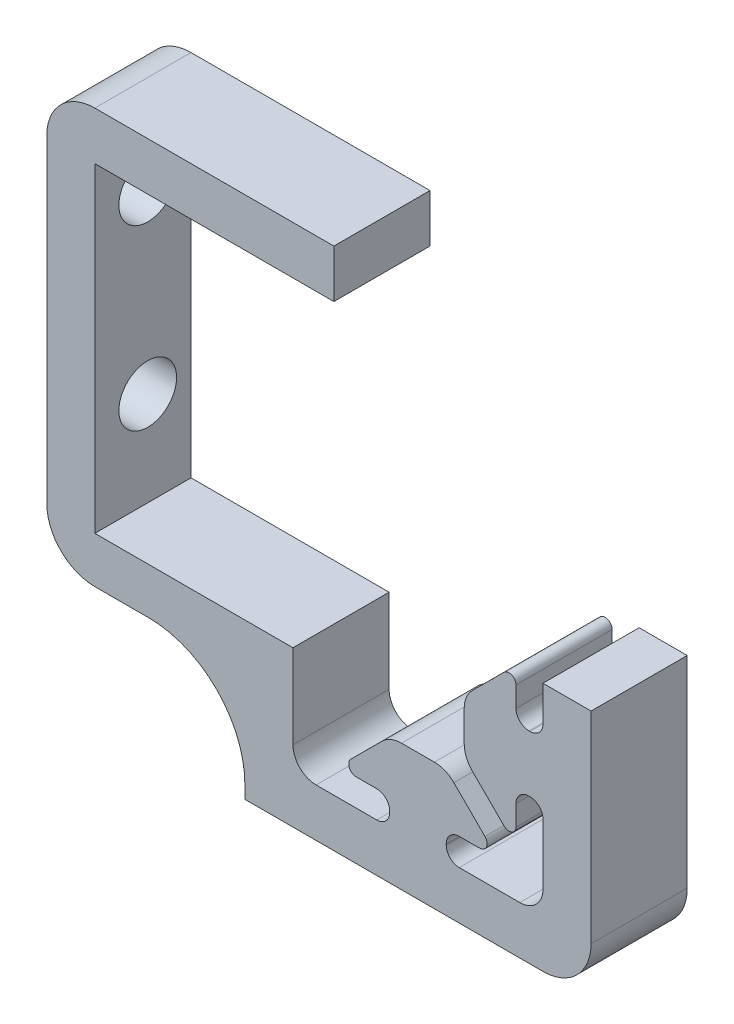
SolidWorks part; units mm, degrees
ref_plane "Front Plane" through (0, 0, 0) normal (0, 0, 1) x (1, 0, 0)
ref_plane "Top Plane" through (0, 0, 0) normal (0, 1, 0) x (1, 0, 0)
ref_plane "Right Plane" through (0, 0, 0) normal (1, 0, 0) x (0, 0, -1)
sketch "Sketch1" plane through (0, 0, 0) normal (0, 0, 1) x (1, 0, 0)
  line L0 (-10.5918, -13) -> (-4.3059, -13)
  line L1 (-4.3059, -13) -> (-4.2875, -13)
  line L2 (-2.9385, -11.651) -> (-2.9385, -11.5392)
  line L3 (-4.2875, -10.1902) -> (-6.4164, -10.1902)
  line L4 (-6.9677, -8.8575) -> (-3.7403, -5.636)
  line L5 (-1.7093, -4.7958) -> (1.7093, -4.7958)
  line L6 (3.7403, -5.636) -> (6.9677, -8.8575)
  line L7 (6.4164, -10.1902) -> (4.2875, -10.1902)
  line L8 (2.9385, -11.5392) -> (2.9385, -11.651)
  line L9 (4.2875, -13) -> (5.3216, -13)
  line L10 (5.3216, -13) -> (10.5918, -13)
  line L11 (13, -10.5918) -> (13, -5.3171)
  line L12 (13, -5.3171) -> (13, -4.2875)
  line L13 (11.651, -2.9385) -> (11.5392, -2.9385)
  line L14 (10.1902, -4.2875) -> (10.1902, -6.4021)
  line L15 (8.949, -6.917) -> (5.6529, -3.6284)
  line L16 (4.8085, -1.5932) -> (4.8085, 1.5932)
  line L17 (5.6529, 3.6284) -> (8.949, 6.917)
  line L18 (10.1902, 6.4021) -> (10.1902, 4.2875)
  line L19 (11.5392, 2.9385) -> (11.651, 2.9385)
  line L20 (13, 4.2875) -> (13, 5.3171)
  line L21 (13, 5.3171) -> (13, 10.5918) construction
  line L22 (10.5918, 13) -> (5.3216, 13) construction
  line L23 (5.3216, 13) -> (4.2875, 13) construction
  line L24 (2.9385, 11.651) -> (2.9385, 11.5392) construction
  line L25 (4.2875, 10.1902) -> (6.4768, 10.1902) construction
  line L26 (6.9951, 8.9367) -> (3.6864, 5.6355) construction
  line L27 (1.6558, 4.7958) -> (-1.6558, 4.7958) construction
  line L28 (-3.6864, 5.6355) -> (-6.9951, 8.9367) construction
  line L29 (-6.4768, 10.1902) -> (-4.2875, 10.1902) construction
  line L30 (-2.9385, 11.5392) -> (-2.9385, 11.651) construction
  line L31 (-4.2875, 13) -> (-4.3059, 13) construction
  line L32 (-4.3059, 13) -> (-10.5918, 13) construction
  line L33 (-13, 10.5918) -> (-13, 5.3171) construction
  line L34 (-13, 5.3171) -> (-13, 4.2875) construction
  line L35 (-11.651, 2.9385) -> (-11.5392, 2.9385) construction
  line L36 (-10.1902, 4.2875) -> (-10.1902, 6.4021) construction
  line L37 (-8.949, 6.917) -> (-5.6529, 3.6284) construction
  line L38 (-4.8085, 1.5932) -> (-4.8085, -1.5932) construction
  line L39 (-5.6529, -3.6284) -> (-8.949, -6.917) construction
  line L40 (-10.1902, -6.4021) -> (-10.1902, -4.2875) construction
  line L41 (-11.5392, -2.9385) -> (-11.651, -2.9385) construction
  line L42 (-13, -4.2875) -> (-13, -10.5918)
  line L44 (13, 5.3171) -> (13, 7.9544)
  line L45 (-33.4, 31.3527) -> (-13, 31.3527) construction
  line L46 (-33.4, 31.3527) -> (-33.4, -1.6473) construction
  line L47 (-33.4, -1.6473) -> (-13, -1.6473) construction
  line L48 (-13, 31.3527) -> (-13, -1.6473) construction
  line L49 (13, 7.9544) -> (18, 7.9544)
  line L50 (18, 7.9544) -> (18, -18)
  line L51 (18, -18) -> (-18, -18)
  line L52 (-18, -18) -> (-18, -6.6473)
  line L53 (-18, -6.6473) -> (-38.6, -6.6473)
  line L54 (-38.6, -6.6473) -> (-38.6, 36.4527)
  line L55 (-38.6, 36.4527) -> (-8.7453, 36.4527)
  line L56 (-8.7453, 36.4527) -> (-8.7453, 31.4527)
  line L57 (-8.7453, 31.4527) -> (-33.6, 31.4527)
  line L58 (-33.6, 31.4527) -> (-33.6, -1.8473)
  line L59 (-33.6, -1.8473) -> (-13, -1.8473)
  line L60 (-13, -1.8473) -> (-13, -4.2875)
  line L88 (-7.1797, -8.6452) -> (-3.9523, -5.4237) construction
  line L89 (-1.7093, -4.4958) -> (1.7093, -4.4958) construction
  line L90 (3.9523, -5.4237) -> (7.1797, -8.6452) construction
  line L91 (6.4164, -10.4902) -> (4.2875, -10.4902) construction
  line L92 (3.2385, -11.5392) -> (3.2385, -11.651) construction
  line L93 (4.2875, -12.7) -> (5.3216, -12.7) construction
  line L94 (5.3216, -12.7) -> (10.5918, -12.7) construction
  line L95 (12.7, -10.5918) -> (12.7, -5.3171) construction
  line L96 (12.7, -5.3171) -> (12.7, -4.2875) construction
  line L97 (11.651, -3.2385) -> (11.5392, -3.2385) construction
  line L98 (10.4902, -4.2875) -> (10.4902, -6.4021) construction
  line L99 (8.7371, -7.1294) -> (5.441, -3.8408) construction
  line L100 (4.5085, -1.5932) -> (4.5085, 1.5932) construction
  line L101 (5.441, 3.8408) -> (8.7371, 7.1294) construction
  line L102 (10.4902, 6.4021) -> (10.4902, 4.2875) construction
  line L103 (11.5392, 3.2385) -> (11.651, 3.2385) construction
  line L104 (12.7, 4.2875) -> (12.7, 5.3171) construction
  line L105 (12.7, 5.3171) -> (12.7, 10.5918) construction
  line L106 (10.5918, 12.7) -> (5.3216, 12.7) construction
  line L107 (5.3216, 12.7) -> (4.2875, 12.7) construction
  line L108 (3.2385, 11.651) -> (3.2385, 11.5392) construction
  line L109 (4.2875, 10.4902) -> (6.4768, 10.4902) construction
  line L110 (7.207, 8.7244) -> (3.8983, 5.4232) construction
  line L111 (1.6558, 4.4958) -> (-1.6558, 4.4958) construction
  line L112 (-3.8983, 5.4232) -> (-7.207, 8.7244) construction
  line L113 (-6.4768, 10.4902) -> (-4.2875, 10.4902) construction
  line L114 (-3.2385, 11.5392) -> (-3.2385, 11.651) construction
  line L115 (-4.2875, 12.7) -> (-4.3059, 12.7) construction
  line L116 (-4.3059, 12.7) -> (-10.5918, 12.7) construction
  line L117 (-12.7, 10.5918) -> (-12.7, 5.3171) construction
  line L118 (-12.7, 5.3171) -> (-12.7, 4.2875) construction
  line L119 (-11.651, 3.2385) -> (-11.5392, 3.2385) construction
  line L120 (-10.4902, 4.2875) -> (-10.4902, 6.4021) construction
  line L121 (-8.7371, 7.1294) -> (-5.441, 3.8408) construction
  line L122 (-4.5085, 1.5932) -> (-4.5085, -1.5932) construction
  line L123 (-5.441, -3.8408) -> (-8.7371, -7.1294) construction
  line L124 (-10.4902, -6.4021) -> (-10.4902, -4.2875) construction
  line L125 (-11.5392, -3.2385) -> (-11.651, -3.2385) construction
  line L126 (-12.7, -4.2875) -> (-12.7, -5.3171) construction
  line L127 (-12.7, -5.3171) -> (-12.7, -10.5918) construction
  line L128 (-10.5918, -12.7) -> (-4.3059, -12.7) construction
  line L129 (-4.3059, -12.7) -> (-4.2875, -12.7) construction
  line L130 (-3.2385, -11.651) -> (-3.2385, -11.5392) construction
  line L131 (-4.2875, -10.4902) -> (-6.4164, -10.4902) construction
  line L132 (-13, -4.2875) -> (-13, -5.3171) construction
  line L133 (-13, -5.3171) -> (-13, -10.5918) construction
  arc A0 (-4.2875, -13) -> (-2.9385, -11.651) centre (-4.2875, -11.651) ccw
  arc A2 (-2.9385, -11.5392) -> (-4.2875, -10.1902) centre (-4.2875, -11.5392) ccw
  arc A3 (-6.9677, -8.8575) -> (-6.4164, -10.1902) centre (-6.4164, -9.4098) ccw
  arc A4 (-1.7093, -4.7958) -> (-3.7403, -5.636) centre (-1.7093, -7.6708) ccw
  arc A5 (3.7403, -5.636) -> (1.7093, -4.7958) centre (1.7093, -7.6708) ccw
  arc A6 (6.4164, -10.1902) -> (6.9677, -8.8575) centre (6.4164, -9.4098) ccw
  arc A7 (4.2875, -10.1902) -> (2.9385, -11.5392) centre (4.2875, -11.5392) ccw
  arc A8 (2.9385, -11.651) -> (4.2875, -13) centre (4.2875, -11.651) ccw
  arc A9 (13, -4.2875) -> (11.651, -2.9385) centre (11.651, -4.2875) ccw
  arc A10 (11.5392, -2.9385) -> (10.1902, -4.2875) centre (11.5392, -4.2875) ccw
  arc A11 (8.949, -6.917) -> (10.1902, -6.4021) centre (9.4628, -6.4021) ccw
  arc A12 (4.8085, -1.5932) -> (5.6529, -3.6284) centre (7.6835, -1.5932) ccw
  arc A13 (5.6529, 3.6284) -> (4.8085, 1.5932) centre (7.6835, 1.5932) ccw
  arc A14 (10.1902, 6.4021) -> (8.949, 6.917) centre (9.4628, 6.4021) ccw
  arc A15 (10.1902, 4.2875) -> (11.5392, 2.9385) centre (11.5392, 4.2875) ccw
  arc A16 (11.651, 2.9385) -> (13, 4.2875) centre (11.651, 4.2875) ccw
  arc A17 (4.2875, 13) -> (2.9385, 11.651) centre (4.2875, 11.651) ccw construction
  arc A18 (2.9385, 11.5392) -> (4.2875, 10.1902) centre (4.2875, 11.5392) ccw construction
  arc A19 (6.9951, 8.9367) -> (6.4768, 10.1902) centre (6.4768, 9.4563) ccw construction
  arc A20 (1.6558, 4.7958) -> (3.6864, 5.6355) centre (1.6558, 7.6708) ccw construction
  arc A21 (-3.6864, 5.6355) -> (-1.6558, 4.7958) centre (-1.6558, 7.6708) ccw construction
  arc A22 (-6.4768, 10.1902) -> (-6.9951, 8.9367) centre (-6.4768, 9.4563) ccw construction
  arc A23 (-4.2875, 10.1902) -> (-2.9385, 11.5392) centre (-4.2875, 11.5392) ccw construction
  arc A24 (-2.9385, 11.651) -> (-4.2875, 13) centre (-4.2875, 11.651) ccw construction
  arc A25 (-13, 4.2875) -> (-11.651, 2.9385) centre (-11.651, 4.2875) ccw construction
  arc A26 (-11.5392, 2.9385) -> (-10.1902, 4.2875) centre (-11.5392, 4.2875) ccw construction
  arc A27 (-8.949, 6.917) -> (-10.1902, 6.4021) centre (-9.4628, 6.4021) ccw construction
  arc A28 (-4.8085, 1.5932) -> (-5.6529, 3.6284) centre (-7.6835, 1.5932) ccw construction
  arc A29 (-5.6529, -3.6284) -> (-4.8085, -1.5932) centre (-7.6835, -1.5932) ccw construction
  arc A30 (-10.1902, -6.4021) -> (-8.949, -6.917) centre (-9.4628, -6.4021) ccw construction
  arc A31 (-10.1902, -4.2875) -> (-11.5392, -2.9385) centre (-11.5392, -4.2875) ccw construction
  arc A32 (-11.651, -2.9385) -> (-13, -4.2875) centre (-11.651, -4.2875) ccw construction
  arc A33 (10.5918, -13) -> (13, -10.5918) centre (10.5918, -10.5918) ccw
  arc A34 (12.9998, 10.5628) -> (10.5628, 12.9998) centre (10.5918, 10.5918) ccw construction
  arc A35 (-10.5628, 12.9998) -> (-12.9998, 10.5628) centre (-10.5918, 10.5918) ccw construction
  arc A36 (-13, -10.5918) -> (-10.5918, -13) centre (-10.5918, -10.5918) ccw
  arc A37 (10.5628, -12.9998) -> (12.9998, -10.5628) centre (10.5918, -10.5918) ccw construction
  arc A38 (-12.9998, -10.5628) -> (-10.5918, -13) centre (-10.5918, -10.5918) ccw construction
  arc A104 (-7.1797, -8.6452) -> (-6.4164, -10.4902) centre (-6.4164, -9.4098) ccw construction
  arc A105 (-1.7093, -4.4958) -> (-3.9523, -5.4237) centre (-1.7093, -7.6708) ccw construction
  arc A106 (3.9523, -5.4237) -> (1.7093, -4.4958) centre (1.7093, -7.6708) ccw construction
  arc A107 (6.4164, -10.4902) -> (7.1797, -8.6452) centre (6.4164, -9.4098) ccw construction
  arc A108 (4.2875, -10.4902) -> (3.2385, -11.5392) centre (4.2875, -11.5392) ccw construction
  arc A109 (3.2385, -11.651) -> (4.2875, -12.7) centre (4.2875, -11.651) ccw construction
  arc A112 (10.5664, -12.6998) -> (12.6998, -10.5664) centre (10.5918, -10.5918) ccw construction
  arc A115 (12.7, -4.2875) -> (11.651, -3.2385) centre (11.651, -4.2875) ccw construction
  arc A116 (11.5392, -3.2385) -> (10.4902, -4.2875) centre (11.5392, -4.2875) ccw construction
  arc A117 (8.7371, -7.1294) -> (10.4902, -6.4021) centre (9.4628, -6.4021) ccw construction
  arc A118 (4.5085, -1.5932) -> (5.441, -3.8408) centre (7.6835, -1.5932) ccw construction
  arc A119 (5.441, 3.8408) -> (4.5085, 1.5932) centre (7.6835, 1.5932) ccw construction
  arc A120 (10.4902, 6.4021) -> (8.7371, 7.1294) centre (9.4628, 6.4021) ccw construction
  arc A121 (10.4902, 4.2875) -> (11.5392, 3.2385) centre (11.5392, 4.2875) ccw construction
  arc A122 (11.651, 3.2385) -> (12.7, 4.2875) centre (11.651, 4.2875) ccw construction
  arc A125 (12.6998, 10.5664) -> (10.5664, 12.6998) centre (10.5918, 10.5918) ccw construction
  arc A128 (4.2875, 12.7) -> (3.2385, 11.651) centre (4.2875, 11.651) ccw construction
  arc A129 (3.2385, 11.5392) -> (4.2875, 10.4902) centre (4.2875, 11.5392) ccw construction
  arc A130 (7.207, 8.7244) -> (6.4768, 10.4902) centre (6.4768, 9.4563) ccw construction
  arc A131 (1.6558, 4.4958) -> (3.8983, 5.4232) centre (1.6558, 7.6708) ccw construction
  arc A132 (-3.8983, 5.4232) -> (-1.6558, 4.4958) centre (-1.6558, 7.6708) ccw construction
  arc A133 (-6.4768, 10.4902) -> (-7.207, 8.7244) centre (-6.4768, 9.4563) ccw construction
  arc A134 (-4.2875, 10.4902) -> (-3.2385, 11.5392) centre (-4.2875, 11.5392) ccw construction
  arc A135 (-3.2385, 11.651) -> (-4.2875, 12.7) centre (-4.2875, 11.651) ccw construction
  arc A138 (-10.5664, 12.6998) -> (-12.6998, 10.5664) centre (-10.5918, 10.5918) ccw construction
  arc A141 (-12.7, 4.2875) -> (-11.651, 3.2385) centre (-11.651, 4.2875) ccw construction
  arc A142 (-11.5392, 3.2385) -> (-10.4902, 4.2875) centre (-11.5392, 4.2875) ccw construction
  arc A143 (-8.7371, 7.1294) -> (-10.4902, 6.4021) centre (-9.4628, 6.4021) ccw construction
  arc A144 (-4.5085, 1.5932) -> (-5.441, 3.8408) centre (-7.6835, 1.5932) ccw construction
  arc A145 (-5.441, -3.8408) -> (-4.5085, -1.5932) centre (-7.6835, -1.5932) ccw construction
  arc A146 (-10.4902, -6.4021) -> (-8.7371, -7.1294) centre (-9.4628, -6.4021) ccw construction
  arc A147 (-10.4902, -4.2875) -> (-11.5392, -3.2385) centre (-11.5392, -4.2875) ccw construction
  arc A148 (-11.651, -3.2385) -> (-12.7, -4.2875) centre (-11.651, -4.2875) ccw construction
  arc A151 (-12.6998, -10.5664) -> (-10.5918, -12.7) centre (-10.5918, -10.5918) ccw construction
  arc A154 (-4.2875, -12.7) -> (-3.2385, -11.651) centre (-4.2875, -11.651) ccw construction
  arc A155 (-3.2385, -11.5392) -> (-4.2875, -10.4902) centre (-4.2875, -11.5392) ccw construction
  dimension "D2" = 33
  dimension "D3" = 20.4
  dimension "D5" = 11.3527
  dimension "D6" = 5
  dimension "D7" = 5
  dimension "D9" = 5
  dimension "D10" = 5
  dimension "D11" = 5
  dimension "D12" = 0.2
  dimension "D13" = 0.2
  dimension ".2" = 0.2
  dimension "D1" = 0.3
extrude "Boss-Extrude1" add sketch "Sketch1" along normal blind 10 contours A36 L42 L60 L59 L58 L57 L56 L55 L54 L53 L52 L51 L50 L49 L44 L20 A16 L19 A15 L18 A14 L17 A13 L16 A12 L15 A11 L14 A10 L13 A9 L12 L11 A33 L10 L9 A8 L8 A7 L7 A6 L6 A5 L5 A4 L4 A3 L3 A2 L2 A0
sketch "Sketch2" plane through (-38.6, 0, 0) normal (-1, 0, 0) x (0, 0, 1)
  line L0 (0, -6.6473) -> (0, 36.4527) construction
  line L3 (4.5, 29.4527) -> (4.5, 26.4527) construction
  line L4 (10, 31.4527) -> (0, 31.4527) construction
  line L5 (4.5, 10.9527) -> (4.5, 4.9527) construction
  line L6 (4.5, 26.4527) -> (4.5, 23.4527) construction
  circle A0 centre (4.5, 26.4527) radius 3
  circle A1 centre (4.5, 7.9527) radius 3
  dimension "D1" = 6
  dimension "D3" = 6
  dimension "D2" = 5
  dimension "D4" = 12.5
  dimension "D5" = 4.5
extrude "Cut-Extrude1" cut sketch "Sketch2" against normal up to next
fillet "Fillet1" radius 10 1 edges at (-18, -6.6473, 5)
fillet "Fillet2" radius 5 3 edges at (18, -18, 5) (-38.6, -6.6473, 5) (-38.6, 36.4527, 5)
